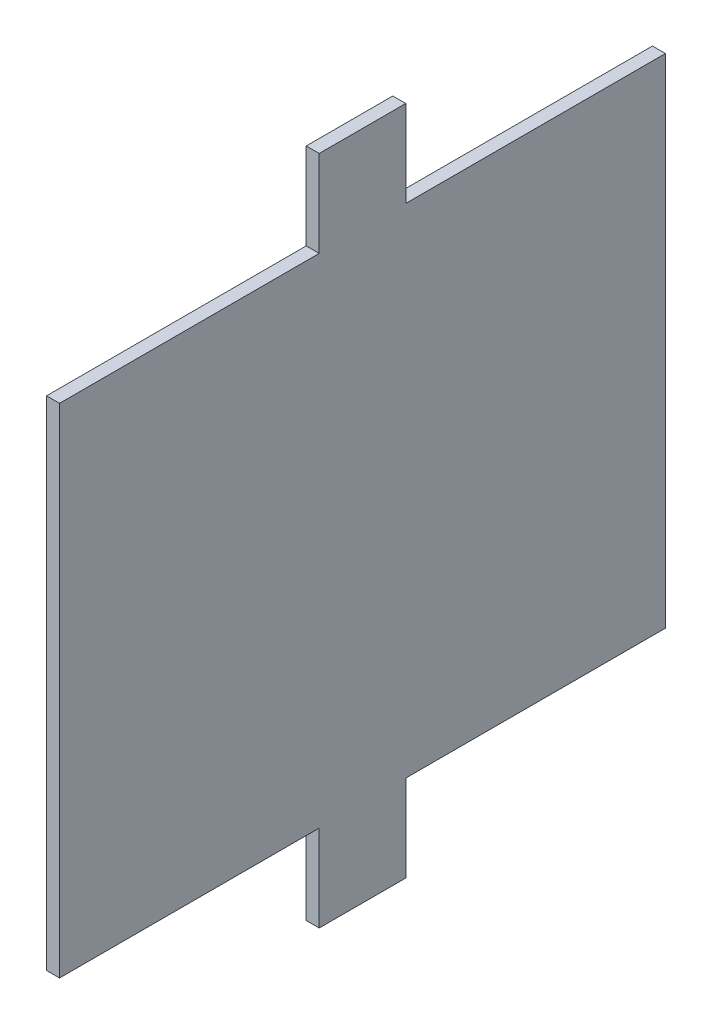
SolidWorks part; units mm, degrees
ref_plane "Front Plane" through (0, 0, 0) normal (0, 0, 1) x (1, 0, 0)
ref_plane "Top Plane" through (0, 0, 0) normal (0, 1, 0) x (1, 0, 0)
ref_plane "Right Plane" through (0, 0, 0) normal (1, 0, 0) x (0, 0, -1)
sketch "Sketch1" plane through (0, 0, 0) normal (1, 0, 0) x (0, 0, -1)
  line L0 (48.7114, 200.8228) -> (201.1114, 200.8228)
  line L1 (-154.4886, 200.8228) -> (-2.0886, 200.8228)
  line L2 (-154.4886, 200.8228) -> (-154.4886, -91.2772)
  line L3 (-154.4886, -91.2772) -> (-2.0886, -91.2772)
  line L4 (201.1114, 200.8228) -> (201.1114, -91.2772)
  line L5 (48.7114, 200.8228) -> (48.7114, 251.6228)
  line L6 (48.7114, 251.6228) -> (-2.0886, 251.6228)
  line L7 (-2.0886, 251.6228) -> (-2.0886, 200.8228)
  line L8 (48.7114, -91.2772) -> (201.1114, -91.2772)
  line L9 (48.7114, -91.2772) -> (48.7114, -142.0772)
  line L10 (48.7114, -142.0772) -> (-2.0886, -142.0772)
  line L11 (-2.0886, -142.0772) -> (-2.0886, -91.2772)
  dimension "D1" = 355.6
  dimension "D2" = 292.1
  dimension "D3" = 50.8
  dimension "D4" = 50.8
  dimension "D5" = 50.8
  dimension "D6" = 50.8
  dimension "D7" = 152.4
  dimension "D8" = 152.4
extrude "Boss-Extrude1" add sketch "Sketch1" along normal mid plane 7.62
sketch "Sketch5" plane through (-3.81, 0, 0) normal (-1, 0, 0) x (0, 0, 1)
